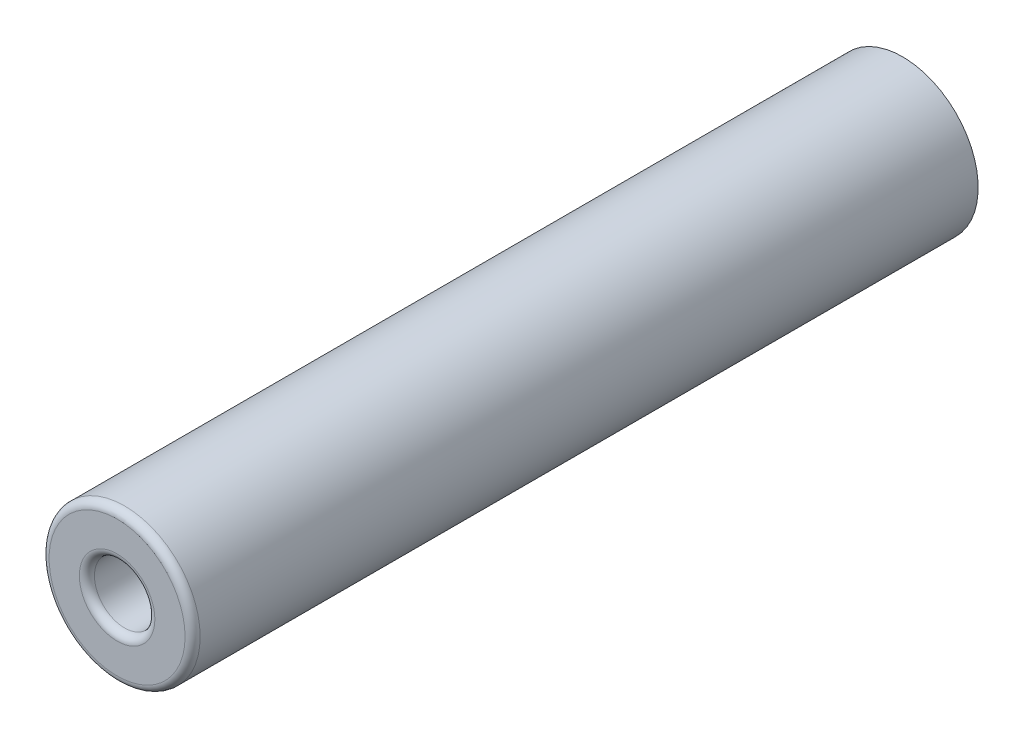
SolidWorks part; units mm, degrees
material "Acero aleado"
ref_plane "Alzado" through (0, 0, 0) normal (0, 0, 1) x (1, 0, 0)
ref_plane "Planta" through (0, 0, 0) normal (0, 1, 0) x (1, 0, 0)
ref_plane "Vista lateral" through (0, 0, 0) normal (1, 0, 0) x (0, 0, -1)
sketch "Croquis1" plane through (0, 0, 0) normal (0, 0, 1) x (1, 0, 0)
  circle A0 centre (0, 0) radius 2.5
  dimension "D1" = 5
extrude "Saliente-Extruir1" add sketch "Croquis1" along normal blind 26
sketch "Croquis2" plane through (0, 0, 26) normal (0, 0, 1) x (1, 0, 0)
  circle A0 centre (0, 0) radius 1
  dimension "D1" = 2
extrude "Cortar-Extruir1" cut sketch "Croquis2" against normal blind 10
fillet "Redondeo1" radius 0.25 2 edges at (2.5, 0, 26) (1, 0, 26)
sketch "Sketch1" plane through (0, 0, 26) normal (0, 0, 1) x (1, 0, 0)
  line L0 (0, 0) -> (0, 24.5) construction
  dimension "D1" = 24.5
